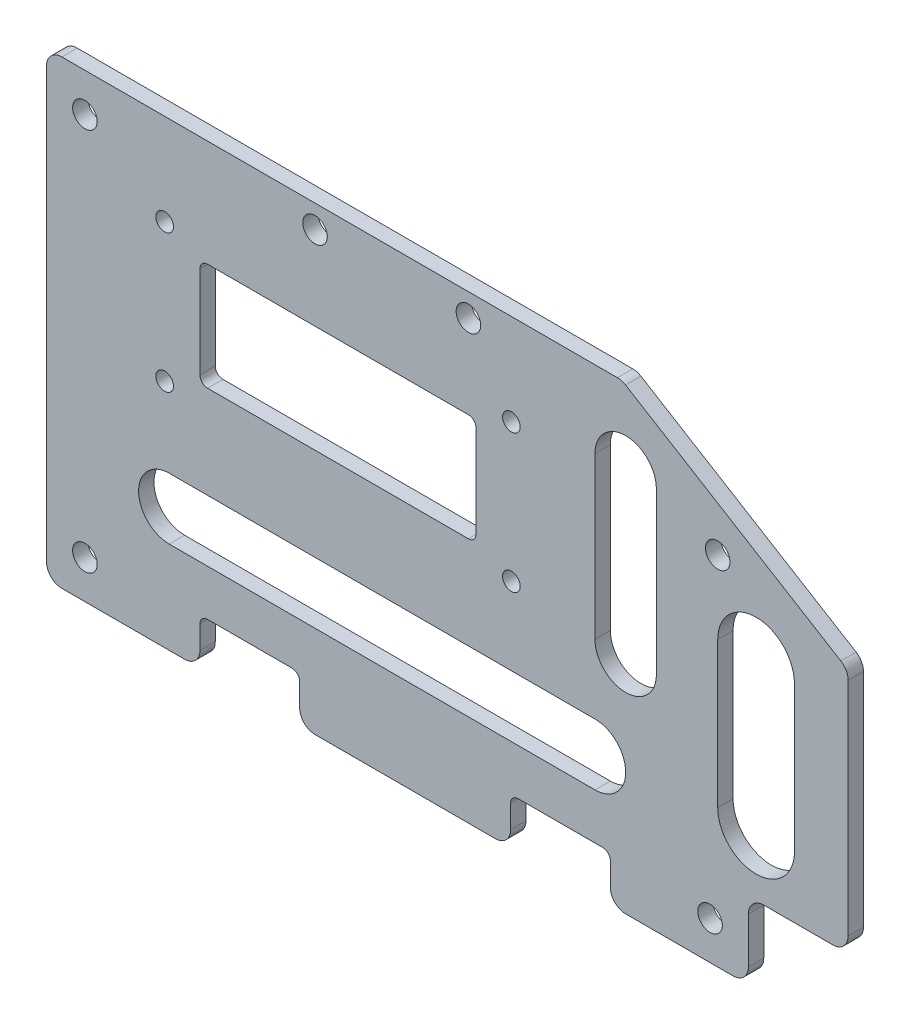
SolidWorks part; units mm, degrees
material "Thornel Mat VMA"
ref_plane "前视基准面" through (0, 0, 0) normal (0, 0, 1) x (1, 0, 0)
ref_plane "上视基准面" through (0, 0, 0) normal (0, 1, 0) x (1, 0, 0)
ref_plane "右视基准面" through (0, 0, 0) normal (1, 0, 0) x (0, 0, -1)
sketch "草图1" plane through (0, 0, 0) normal (0, 0, 1) x (1, 0, 0)
  line L0 (0, 0) -> (0, 60)
  line L2 (91.5, 10) -> (91.5, 0)
  line L3 (91.5, 0) -> (73.5, 0)
  line L4 (91.5, 10) -> (104.5, 10)
  line L5 (104.5, 10) -> (104.5, 42)
  line L6 (104.5, 42) -> (75, 60)
  line L7 (75, 60) -> (0, 60)
  line L8 (73.5, 0) -> (73.5, 6)
  line L9 (73.5, 6) -> (60.5, 6)
  line L10 (60.5, 6) -> (60.5, 0)
  line L11 (20, 0) -> (20, 6)
  line L12 (20, 6) -> (33, 6)
  line L13 (33, 6) -> (33, 0)
  line L14 (60.5, 0) -> (33, 0)
  line L15 (20, 0) -> (0, 0)
  line L16 (71.5, 16) -> (16, 16) construction
  line L17 (71.5, 12) -> (16, 12)
  line L18 (71.5, 20) -> (16, 20)
  line L19 (38, 52) -> (38, 26.2) construction
  line L20 (17.5, 52) -> (58.5, 52) construction
  line L21 (17.5, 26.2) -> (58.5, 26.2) construction
  line L22 (62.7, 39.1) -> (13.3, 39.1) construction
  line L23 (62.7, 30.1) -> (62.7, 48.1) construction
  line L24 (13.3, 30.1) -> (13.3, 48.1) construction
  line L26 (20, 32.1) -> (56, 32.1)
  line L27 (20, 32.1) -> (20, 46.1)
  line L28 (20, 46.1) -> (56, 46.1)
  line L29 (56, 32.1) -> (56, 46.1)
  line L30 (20, 32.1) -> (56, 46.1) construction
  line L31 (20, 46.1) -> (56, 32.1) construction
  circle A0 centre (86.5, 5) radius 1.6
  circle A1 centre (5, 5) radius 1.6
  circle A2 centre (60.6, 48.1) radius 1.15
  circle A3 centre (60.6, 30.1) radius 1.15
  circle A4 centre (15.4, 48.1) radius 1.15
  circle A5 centre (15.4, 30.1) radius 1.15
  arc A6 (71.5, 12) -> (71.5, 20) centre (71.5, 16) ccw
  arc A7 (16, 20) -> (16, 12) centre (16, 16) ccw
  circle A8 centre (87.5, 46.5156) radius 1.6
  circle A9 centre (55, 57) radius 1.6
  circle A10 centre (35, 57) radius 1.6
  circle A11 centre (5, 55) radius 1.6
  point P34 (43.75, 16)
  point P51 (38, 39.1)
  dimension "D3" = 3.2
  dimension "D6" = 3.2
  dimension "D19" = 2.3
  dimension "D20" = 2.3
  dimension "D21" = 2.3
  dimension "D22" = 2.3
  dimension "D29" = 3.2
  dimension "D32" = 3.2
  dimension "D33" = 3.2
  dimension "D1" = 91.5
  dimension "D2" = 10
  dimension "D4" = 5
  dimension "D5" = 5
  dimension "D7" = 5
  dimension "D8" = 5
  dimension "D9" = 13
  dimension "D10" = 32
  dimension "D11" = 60
  dimension "D12" = 75
  dimension "D13" = 18
  dimension "D14" = 13
  dimension "D15" = 6
  dimension "D16" = 20
  dimension "D17" = 13
  dimension "D18" = 6
  dimension "D23" = 16
  dimension "D24" = 8
  dimension "D25" = 20
  dimension "D26" = 16
  dimension "D27" = 36
  dimension "D28" = 14
  dimension "D30" = 17
  dimension "D31" = 5
extrude "凸台-拉伸1" add sketch "草图1" along normal blind 2
sketch "草图2" plane through (0, 0, 0) normal (0, 0, -1) x (-1, 0, 0)
  line L0 (-92.5, 37) -> (-92.5, 18) construction
  line L1 (-87.5, 37) -> (-87.5, 18)
  line L2 (-97.5, 37) -> (-97.5, 18)
  line L3 (-104.5, 10) -> (-104.5, 42) construction
  line L5 (-91.5, 10) -> (-104.5, 10) construction
  line L6 (-75.5, 50) -> (-75.5, 29) construction
  line L7 (-71.5, 50) -> (-71.5, 29)
  line L8 (-79.5, 50) -> (-79.5, 29)
  line L9 (-75, 60) -> (0, 60) construction
  arc A0 (-87.5, 37) -> (-97.5, 37) centre (-92.5, 37) ccw
  arc A1 (-97.5, 18) -> (-87.5, 18) centre (-92.5, 18) ccw
  arc A2 (-71.5, 50) -> (-79.5, 50) centre (-75.5, 50) ccw
  arc A3 (-79.5, 29) -> (-71.5, 29) centre (-75.5, 29) ccw
  point P2 (-92.5, 27.5)
  point P14 (-75.5, 39.5)
  dimension "D1" = 12
  dimension "D2" = 8
  dimension "D3" = 5
  dimension "D4" = 10
  dimension "D5" = 17
  dimension "D6" = 10
  dimension "D7" = 21
  dimension "D8" = 8
extrude "切除-拉伸1" cut sketch "草图2" against normal through all
fillet "圆角1" radius 2 11 edges at (91.5, 0, 1) (0, 0, 1) (0, 60, 1) (75, 60, 1) (104.5, 42, 1) (104.5, 10, 1) (91.5, 10, 1) (33, 0, 1) (20, 0, 1) (60.5, 0, 1) (73.5, 0, 1)
fillet "圆角2" radius 1 4 edges at (56, 46.1, 1) (56, 32.1, 1) (20, 32.1, 1) (20, 46.1, 1)
fillet "圆角3" radius 1 4 edges at (20, 6, 1) (33, 6, 1) (73.5, 6, 1) (60.5, 6, 1)
